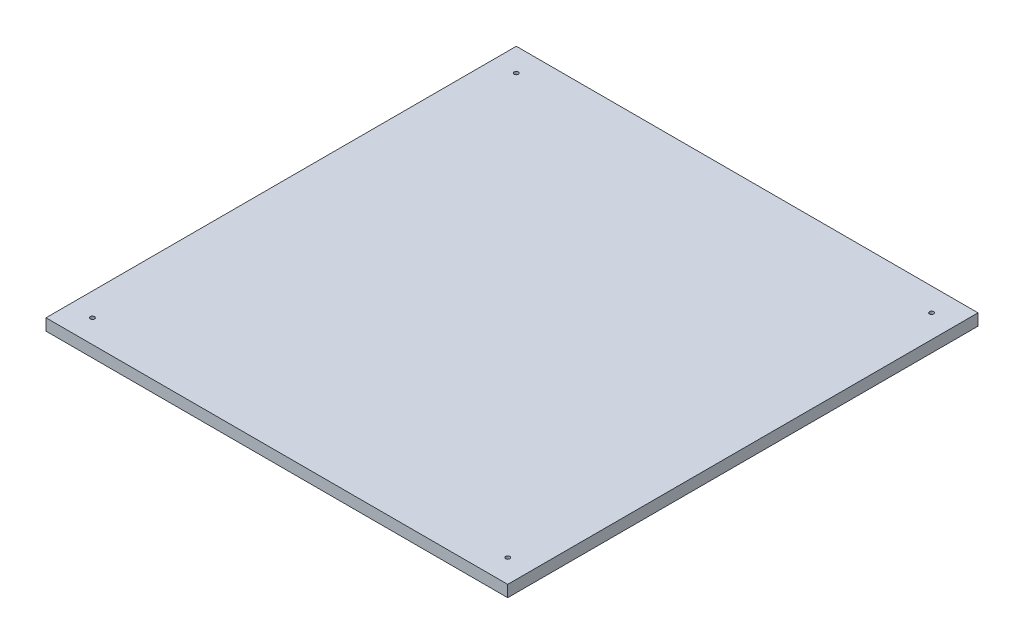
SolidWorks part; units mm, degrees
ref_plane "Front Plane" through (0, 0, 0) normal (0, 0, 1) x (1, 0, 0)
ref_plane "Top Plane" through (0, 0, 0) normal (0, 1, 0) x (1, 0, 0)
ref_plane "Right Plane" through (0, 0, 0) normal (1, 0, 0) x (0, 0, -1)
sketch "Sketch1" plane through (0, 0, 0) normal (0, 1, 0) x (1, 0, 0)
  line L1 (-298.45, -304.0063) -> (298.45, -304.0063)
  line L2 (-298.45, -304.0063) -> (-298.45, 304.0062)
  line L3 (-298.45, 304.0062) -> (298.45, 304.0062)
  line L4 (298.45, -304.0063) -> (298.45, 304.0062)
  line L5 (-298.45, -304.0063) -> (298.45, 304.0062) construction
  line L6 (-298.45, 304.0062) -> (298.45, -304.0063) construction
  point P0 (0, 0)
  dimension "D1" = 608.0125
  dimension "D2" = 596.9
extrude "Boss-Extrude1" add sketch "Sketch1" along normal blind 15
ref_plane "Plane1" through (-298.45, 15, -304.0062) normal (-1, 0, 0) x (0, 0, 1)
sketch "construction lines" plane through (0, 15, 0) normal (0, 1, 0) x (1, 0, 0)
  line L0 (-268.45, 304.0062) -> (-268.45, -304.0063) construction
  line L1 (298.45, 304.0062) -> (-298.45, 304.0062) construction
  line L2 (-298.45, -304.0063) -> (298.45, -304.0063) construction
  line L3 (-298.45, -274.0063) -> (298.45, -274.0062) construction
  line L4 (-298.45, 304.0062) -> (-298.45, -304.0063) construction
  line L5 (298.45, -304.0063) -> (298.45, 304.0062) construction
  line L6 (-298.45, 274.0062) -> (298.45, 274.0062) construction
  line L7 (-298.45, 468.1537) -> (-298.45, 139.8587) construction
  line L8 (268.45, 304.0062) -> (268.45, -304.0063) construction
  line L9 (-298.45, 0) -> (298.45, 0) construction
  line L10 (0, -304.0063) -> (0, 304.0062) construction
  dimension "D1" = 30
  dimension "D2" = 30
  dimension "D3" = 30
  dimension "D4" = 30
hole_wizard "1/4-28 Tapped Hole1" positions "3DSketch2" profile "Sketch4" tap size "1/4-28" standard "ANSI Inch" end condition through all
sketch3d "3DSketch2"
  line L0 (-268.45, 15, -304.0062) -> (-268.45, 15, 304.0063) construction
  line L1 (-298.45, 15, 274.0063) -> (298.45, 15, 274.0062) construction
  line L2 (-298.45, 15, -274.0062) -> (298.45, 15, -274.0062) construction
  line L3 (268.45, 15, -304.0062) -> (268.45, 15, 304.0063) construction
  point P0 (-268.45, 15, 274.0063)
  point P6 (-268.45, 15, -274.0062)
  point P10 (268.45, 15, -274.0062)
  point P14 (268.45, 15, 274.0062)
sketch "Sketch4" plane through (-268.45, 15, 274.0063) normal (1, 0, 0) x (0, 0, 1)
  line L0 (0, 0) -> (0, 15)
  line L1 (0, 15) -> (2.7051, 15)
  line L2 (2.7051, 15) -> (2.7051, 0)
  line L5 (2.7051, 0) -> (0, 0)
  line L11 (0, -6.35) -> (0, 107.95) construction
  dimension "Thread Major Dia." = 5.4102
  dimension "Thru Tap Drill Depth" = 15
equation "\"D1@construction lines\" = \"holeWidthFromEdge@table assembly.Assembly\""
equation "\"D4@construction lines\" = \"holeWidthFromEdge@table assembly.Assembly\""
equation "\"D3@construction lines\" = \"holeWidthFromEdge@table assembly.Assembly\""
equation "\"D2@construction lines\" = \"holeWidthFromEdge@table assembly.Assembly\""
